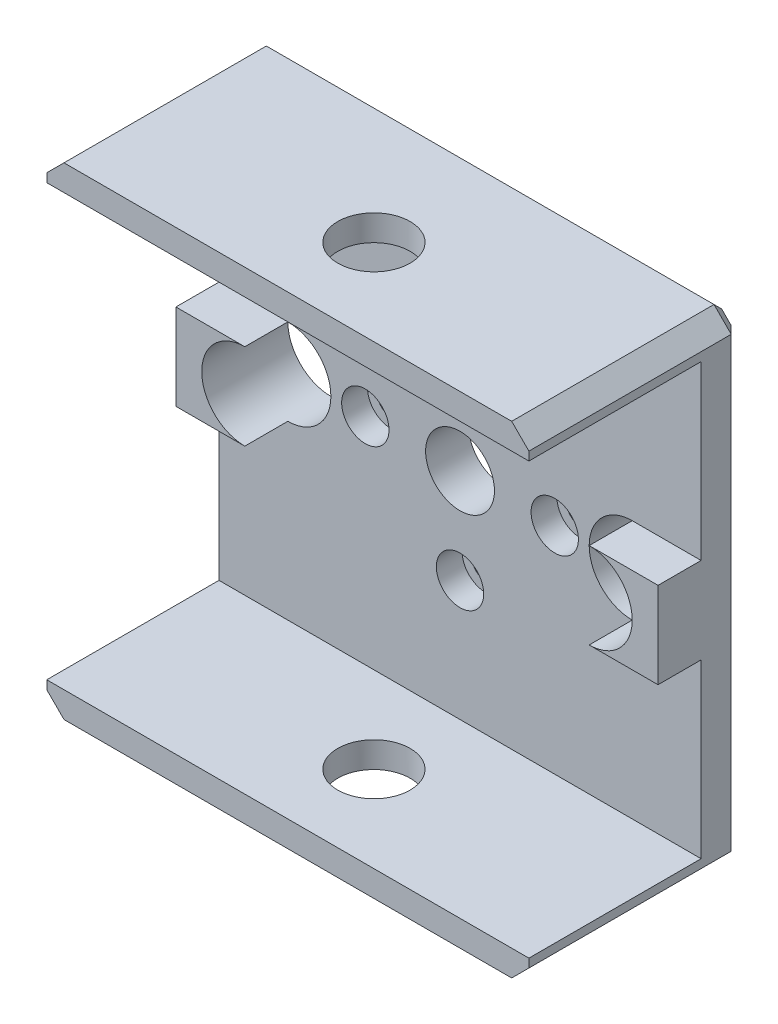
SolidWorks part; units mm, degrees
ref_plane "Alzado" through (0, 0, 0) normal (0, 0, 1) x (1, 0, 0)
ref_plane "Planta" through (0, 0, 0) normal (0, 1, 0) x (1, 0, 0)
ref_plane "Vista lateral" through (0, 0, 0) normal (1, 0, 0) x (0, 0, -1)
sketch "Croquis1" plane through (0, 0, 0) normal (0, 0, 1) x (1, 0, 0)
  line L0 (0, 0.8576) -> (0, 50000.8576) construction
  line L2 (-28, 28) -> (28, 28)
  line L3 (-28, 28) -> (-28, -28)
  line L4 (-28, -28) -> (28, -28)
  line L5 (28, 28) -> (28, -28)
  circle A0 centre (0, 0) radius 4
  circle A1 centre (0, 11) radius 1.6
  circle A2 centre (11, 0) radius 1.6
  circle A3 centre (0, -11) radius 1.6
  circle A4 centre (-11, 0) radius 1.6
  point P16 (0, 0)
  point P18 (0, 28)
  dimension "D1" = 8
  dimension "D2" = 3.2
  dimension "D3" = 11
  dimension "D5" = 28
  dimension "D6" = 56
  dimension "D7" = 56
  dimension "D4" = 4
extrude "Saliente-Extruir1" add sketch "Croquis1" along normal blind 5
sketch "Croquis2" plane through (0, 0, 5) normal (0, 0, 1) x (1, 0, 0)
  line L0 (28, -28) -> (28, 28) construction
  line L1 (-28, 28) -> (28, 28)
  line L2 (-28, 28) -> (-28, 25)
  line L3 (-28, 25) -> (28, 25)
  line L4 (28, 28) -> (28, 25)
  line L5 (-28, 28) -> (28, 25) construction
  line L6 (-28, 25) -> (28, 28) construction
  line L8 (-28, -28) -> (28, -28)
  line L9 (-28, -28) -> (-28, -25)
  line L10 (-28, -25) -> (28, -25)
  line L11 (28, -28) -> (28, -25)
  line L12 (-28, -28) -> (28, -25) construction
  line L13 (-28, -25) -> (28, -28) construction
  point P4 (0, 26.5)
  point P12 (0, -26.5)
  dimension "D1" = 3
extrude "Saliente-Extruir2" add sketch "Croquis2" along normal blind 20
sketch "Croquis3" plane through (0, 28, 0) normal (0, 1, 0) x (1, 0, 0)
  line L0 (0, 0) -> (0, -50000) construction
  line L1 (28, 0) -> (-28, 0) construction
  circle A0 centre (0, -15) radius 4.2
  dimension "D1" = 8.4
  dimension "D2" = 15
extrude "Cortar-Extruir1" cut sketch "Croquis3" against normal through all
sketch "Croquis4" plane through (0, 0, 5) normal (0, 0, 1) x (1, 0, 0)
  circle A0 centre (-11, 0) radius 2.75
  circle A1 centre (0, 11) radius 2.75
  circle A2 centre (11, 0) radius 2.75
  circle A3 centre (0, -11) radius 2.75
  dimension "D1" = 5.5
extrude "Cortar-Extruir2" cut sketch "Croquis4" against normal blind 3
sketch "Croquis7" plane through (0, 0, 5) normal (0, 0, 1) x (1, 0, 0)
  line L0 (0, 0) -> (-50000, 0) construction
  line L1 (-28, 25) -> (-28, -25) construction
  line L2 (-28, -5) -> (-20, -5)
  line L3 (-28, -5) -> (-28, 5)
  line L4 (-28, 5) -> (-20, 5)
  line L5 (-20, -5) -> (-20, 5)
  line L6 (-28, -5) -> (-20, 5) construction
  line L7 (-28, 5) -> (-20, -5) construction
  point P3 (-24, 0)
  point P8 (-28, 8.2681)
  dimension "D1" = 10
  dimension "D2" = 8
extrude "Saliente-Extruir3" add sketch "Croquis7" along normal blind 5
mirror "Simetría2" about plane through (0, 0, 0) normal (1, 0, 0) of "Saliente-Extruir3"
sketch "Croquis5" plane through (0, 0, 0) normal (0, 0, -1) x (-1, 0, 0)
  line L0 (0, 0) -> (50000, 0) construction
  line L1 (0, 0) -> (0, 50000) construction
  circle A0 centre (20, 0) radius 5
  point P8 (20.8335, 0)
  dimension "D1" = 20
  dimension "D2" = 10
extrude "Cortar-Extruir3" cut sketch "Croquis5" against normal through all
mirror "Simetría1" about plane through (0, 0, 0) normal (1, 0, 0) of "Cortar-Extruir3"
chamfer "Chaflán1" distance 2 angle 45 4 edges at (28, -28, 12.5) (28, 28, 12.5) (-28, -28, 12.5) (-28, 28, 12.5)
chamfer "Chaflán2" distance 1.5 angle 45 8 edges at (27, 27, 0) (0, 28, 0) (-27, 27, 0) (-28, 0, 0) (-27, -27, 0) (0, -28, 0) (27, -27, 0) (28, 0, 0)
